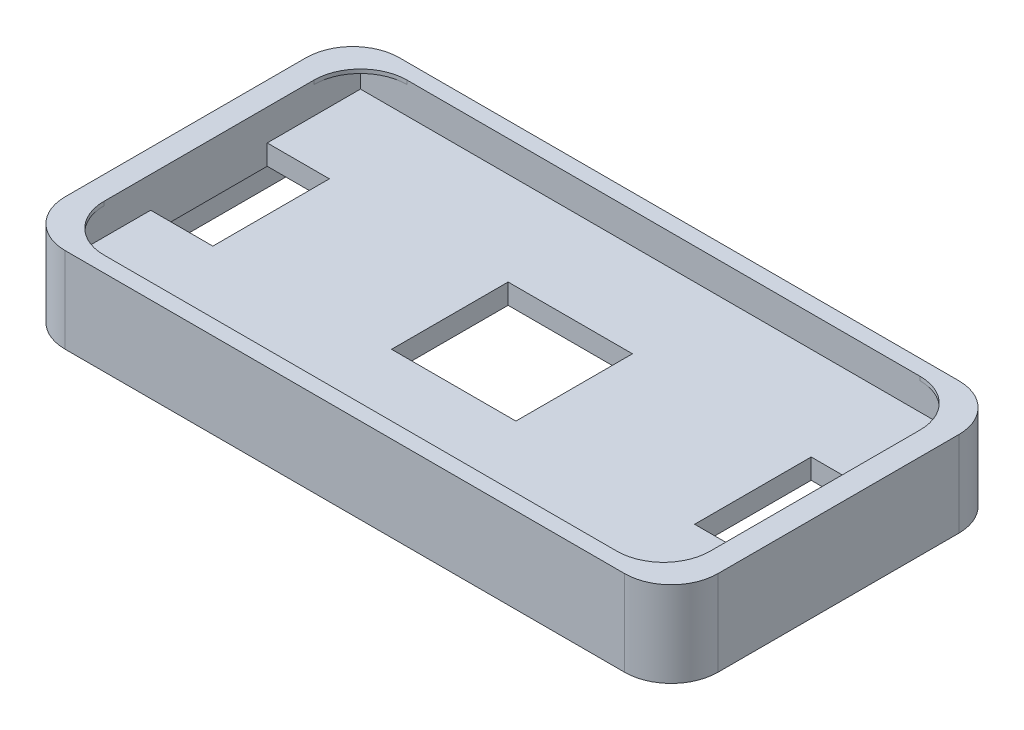
SolidWorks part; units mm, degrees
material "ABS"
ref_plane "前视基准面" through (0, 0, 0) normal (0, 0, 1) x (1, 0, 0)
ref_plane "上视基准面" through (0, 0, 0) normal (0, 1, 0) x (1, 0, 0)
ref_plane "右视基准面" through (0, 0, 0) normal (1, 0, 0) x (0, 0, -1)
sketch "草图1" plane through (0, 0, 0) normal (0, 1, 0) x (1, 0, 0)
  line L1 (-36, 21.5) -> (36, 21.5)
  line L2 (-42, 15.5) -> (-42, -15.5)
  line L3 (-36, -21.5) -> (36, -21.5)
  line L4 (42, 15.5) -> (42, -15.5)
  line L5 (-42, 21.5) -> (42, -21.5) construction
  line L6 (-42, -21.5) -> (42, 21.5) construction
  arc A0 (36, -21.5) -> (42, -15.5) centre (36, -15.5) ccw
  arc A1 (-42, -15.5) -> (-36, -21.5) centre (-36, -15.5) ccw
  arc A2 (36, 21.5) -> (42, 15.5) centre (36, 15.5) cw
  arc A3 (-36, 21.5) -> (-42, 15.5) centre (-36, 15.5) ccw
  point P0 (0, 0)
  dimension "D3" = 6
  dimension "D1" = 84
  dimension "D2" = 43
extrude "凸台-拉伸1" add sketch "草图1" along normal blind 10.5
sketch "草图2" plane through (0, 0, 0) normal (0, -1, 0) x (1, 0, 0)
  line L8 (36, 20.5) -> (-36, 20.5)
  line L9 (-41, 15.5) -> (-41, -15.5)
  line L10 (-36, -20.5) -> (36, -20.5)
  line L11 (41, -15.5) -> (41, 15.5)
  line L12 (36, 20.5) -> (-36, 20.5)
  line L13 (-41, 15.5) -> (-41, -15.5)
  line L14 (-36, -20.5) -> (36, -20.5)
  line L15 (41, -15.5) -> (41, 15.5)
  arc A8 (41, 15.5) -> (36, 20.5) centre (36, 15.5) ccw
  arc A9 (-36, 20.5) -> (-41, 15.5) centre (-36, 15.5) ccw
  arc A10 (-41, -15.5) -> (-36, -20.5) centre (-36, -15.5) ccw
  arc A11 (36, -20.5) -> (41, -15.5) centre (36, -15.5) ccw
  arc A12 (41, 15.5) -> (36, 20.5) centre (36, 15.5) ccw
  arc A13 (-36, 20.5) -> (-41, 15.5) centre (-36, 15.5) ccw
  arc A14 (-41, -15.5) -> (-36, -20.5) centre (-36, -15.5) ccw
  arc A15 (36, -20.5) -> (41, -15.5) centre (36, -15.5) ccw
  dimension "D1" = 1
extrude "切除-拉伸1" cut sketch "草图2" against normal blind 1
sketch "草图3" plane through (0, 1, 0) normal (0, -1, 0) x (-1, 0, 0)
  line L0 (0, 0) -> (0, -18.2209) construction
  line L1 (0, 0) -> (28.1035, 0) construction
  line L6 (-36, -20.5) -> (36, -20.5)
  line L7 (41, -15.5) -> (41, 15.5)
  line L8 (36, 20.5) -> (-36, 20.5)
  line L9 (-41, 15.5) -> (-41, -15.5)
  line L10 (-36, -20.5) -> (36, -20.5)
  line L11 (41, -15.5) -> (41, 15.5)
  line L12 (36, 20.5) -> (-36, 20.5)
  line L13 (-41, 15.5) -> (-41, -15.5)
  circle A0 centre (36, -15.5) radius 2.5
  circle A1 centre (36, 15.5) radius 2.5
  circle A2 centre (-36, 15.5) radius 2.5
  circle A3 centre (-36, -15.5) radius 2.5
  circle A4 centre (36, -15.5) radius 1.65
  circle A5 centre (36, 15.5) radius 1.65
  circle A6 centre (-36, -15.5) radius 1.65
  circle A7 centre (-36, 15.5) radius 1.65
  arc A12 (-41, -15.5) -> (-36, -20.5) centre (-36, -15.5) ccw
  arc A13 (36, -20.5) -> (41, -15.5) centre (36, -15.5) ccw
  arc A14 (41, 15.5) -> (36, 20.5) centre (36, 15.5) ccw
  arc A15 (-36, 20.5) -> (-41, 15.5) centre (-36, 15.5) ccw
  arc A16 (-41, -15.5) -> (-36, -20.5) centre (-36, -15.5) ccw
  arc A17 (36, -20.5) -> (41, -15.5) centre (36, -15.5) ccw
  arc A18 (41, 15.5) -> (36, 20.5) centre (36, 15.5) ccw
  arc A19 (-36, 20.5) -> (-41, 15.5) centre (-36, 15.5) ccw
  arc M11 (-41, -15.5) -> (-36, -20.5) centre (-36, -15.5) ccw
  line M12 (-36, -20.5) -> (36, -20.5)
  arc M13 (36, -20.5) -> (41, -15.5) centre (36, -15.5) ccw
  line M14 (41, -15.5) -> (41, 15.5)
  arc M15 (41, 15.5) -> (36, 20.5) centre (36, 15.5) ccw
  line M16 (36, 20.5) -> (-36, 20.5)
  arc M17 (-36, 20.5) -> (-41, 15.5) centre (-36, 15.5) ccw
  line M18 (-41, 15.5) -> (-41, -15.5)
  dimension "D1" = 5
  dimension "D2" = 3.3
  dimension "D3" = 0
extrude "切除-拉伸2" cut sketch "草图3" against normal blind 3.4 contours A1 A0 A2 A3 M18 M11 M12 M13 M14 M15 M16 M17 | A5 | A4 | A6 | A7
sketch "草图4" plane through (0, 10.5, 0) normal (0, 1, 0) x (1, 0, 0)
  line L0 (0, 0) -> (22.2653, 0) construction
  line L1 (0, -0.4893) -> (0, 16.5766) construction
  line L3 (-39, 19.5) -> (39, 19.5)
  line L4 (-39, 19.5) -> (-39, -19.5)
  line L5 (-39, -19.5) -> (39, -19.5)
  line L6 (39, 19.5) -> (39, -19.5)
  line L7 (-39, 19.5) -> (39, -19.5) construction
  line L8 (-39, -19.5) -> (39, 19.5) construction
  dimension "D1" = 39
  dimension "D2" = 78
extrude "切除-拉伸3" cut sketch "草图4" against normal blind 3.5
sketch "草图5" plane through (0, 7, 0) normal (0, 1, 0) x (1, 0, 0)
  line L0 (-39, 0) -> (39, 0) construction
  line L1 (-39, 19.5) -> (-39, -19.5) construction
  line L2 (39, -19.5) -> (39, 19.5) construction
  line L3 (-39, 19.5) -> (-39, -19.5) construction
  line L4 (-31, 7.5) -> (-39, 7.5)
  line L5 (-31, 7.5) -> (-31, -7.5)
  line L6 (-31, -7.5) -> (-39, -7.5)
  line L7 (-39, 7.5) -> (-39, -7.5)
  line L8 (-31, 7.5) -> (-39, -7.5) construction
  line L9 (-31, -7.5) -> (-39, 7.5) construction
  line L10 (0, 0) -> (0, 17.3107) construction
  line L11 (31, -7.5) -> (39, -7.5)
  line L12 (31, 7.5) -> (39, 7.5)
  line L13 (39, 7.5) -> (39, -7.5)
  line L14 (31, 7.5) -> (31, -7.5)
  point P6 (-35, 0)
  dimension "D1" = 15
  dimension "D2" = 8
extrude "切除-拉伸4" cut sketch "草图5" against normal through all
sketch "草图6" plane through (0, 7, 0) normal (0, 1, 0) x (1, 0, 0)
  line L0 (-14.5581, 0) -> (14.0076, 0) construction
  line L1 (0, 12.9065) -> (0, -12.2948) construction
  line L3 (-8, 7.5) -> (8, 7.5)
  line L4 (-8, 7.5) -> (-8, -7.5)
  line L5 (-8, -7.5) -> (8, -7.5)
  line L6 (8, 7.5) -> (8, -7.5)
  line L7 (-8, 7.5) -> (8, -7.5) construction
  line L8 (-8, -7.5) -> (8, 7.5) construction
  point P5 (0, 0)
  dimension "D1" = 16
  dimension "D2" = 15
extrude "切除-拉伸5" cut sketch "草图6" against normal through all
sketch "草图7" plane through (0, 10.5, 0) normal (0, 1, 0) x (1, 0, 0)
  line L0 (-39, -19.5) -> (39, -19.5) construction
  line L1 (39, -19.5) -> (39, 19.5) construction
  line L2 (39, 19.5) -> (-39, 19.5) construction
  line L3 (-39, 19.5) -> (-39, -19.5) construction
  line L4 (-33, -19.5) -> (33, -19.5)
  line L5 (39, -13.5) -> (39, 13.5)
  line L6 (33, 19.5) -> (-33, 19.5)
  line L7 (-39, 13.5) -> (-39, -13.5)
  line L12 (42, -15.5) -> (42, 15.5)
  line L13 (36, 21.5) -> (-36, 21.5)
  line L14 (-42, 15.5) -> (-42, -15.5)
  line L15 (-36, -21.5) -> (36, -21.5)
  line L16 (42, -15.5) -> (42, 15.5)
  line L17 (36, 21.5) -> (-36, 21.5)
  line L18 (-42, 15.5) -> (-42, -15.5)
  line L19 (-36, -21.5) -> (36, -21.5)
  arc A1 (-33, -19.5) -> (-39, -13.5) centre (-33, -13.5) cw
  arc A2 (-33, 19.5) -> (-39, 13.5) centre (-33, 13.5) ccw
  arc A3 (39, 13.5) -> (33, 19.5) centre (33, 13.5) ccw
  arc A4 (33, -19.5) -> (39, -13.5) centre (33, -13.5) ccw
  arc A9 (36, -21.5) -> (42, -15.5) centre (36, -15.5) ccw
  arc A10 (42, 15.5) -> (36, 21.5) centre (36, 15.5) ccw
  arc A11 (-36, 21.5) -> (-42, 15.5) centre (-36, 15.5) ccw
  arc A12 (-42, -15.5) -> (-36, -21.5) centre (-36, -15.5) ccw
  arc A13 (36, -21.5) -> (42, -15.5) centre (36, -15.5) ccw
  arc A14 (42, 15.5) -> (36, 21.5) centre (36, 15.5) ccw
  arc A15 (-36, 21.5) -> (-42, 15.5) centre (-36, 15.5) ccw
  arc A16 (-42, -15.5) -> (-36, -21.5) centre (-36, -15.5) ccw
  dimension "D1" = 6
  dimension "D2" = 0
extrude "凸台-拉伸2" add sketch "草图7" along normal blind 0.5
